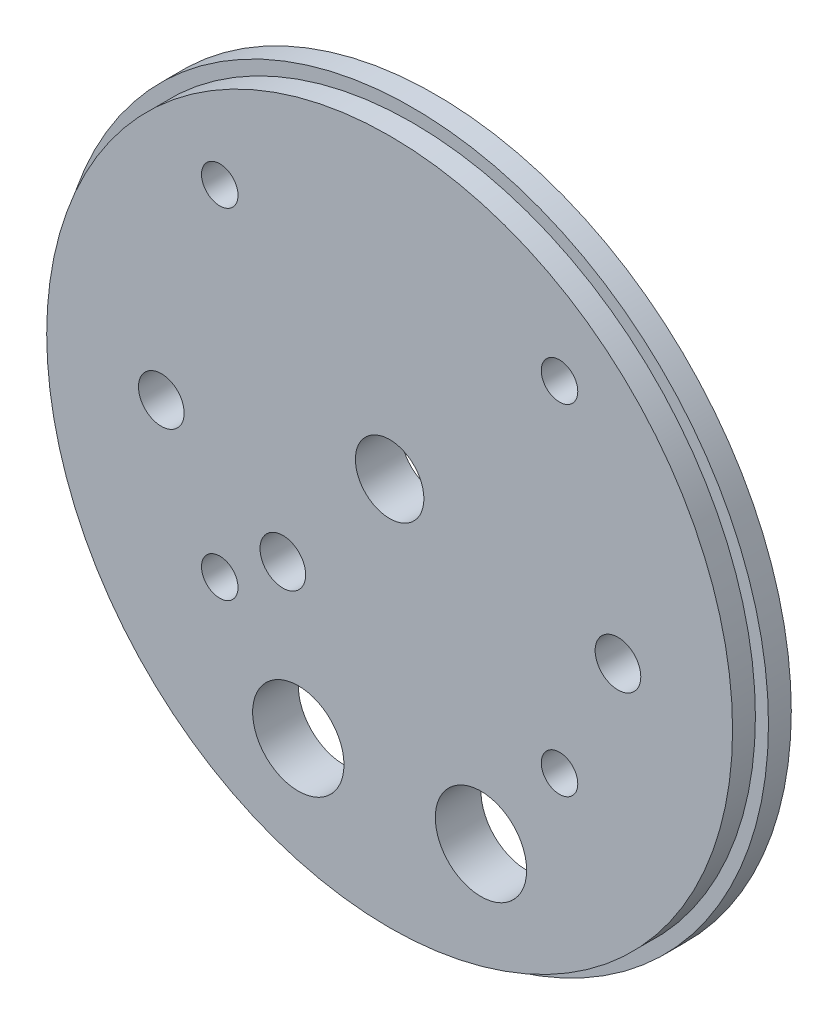
SolidWorks part; units mm, degrees
ref_plane "Front Plane" through (0, 0, 0) normal (0, 0, 1) x (1, 0, 0)
ref_plane "Top Plane" through (0, 0, 0) normal (0, 1, 0) x (1, 0, 0)
ref_plane "Right Plane" through (0, 0, 0) normal (1, 0, 0) x (0, 0, -1)
sketch "Sketch1" plane through (0, 0, 0) normal (0, 0, 1) x (1, 0, 0)
  circle A0 centre (0, 0) radius 49.5046
  point P3 (0, 0)
  dimension "D1" = 99.0092
extrude "Boss-Extrude1" add sketch "Sketch1" along normal blind 3.175
sketch "Sketch2" plane through (0, 0, 3.175) normal (0, 0, 1) x (1, 0, 0)
  circle A0 centre (0, 0) radius 47.6885
  dimension "D1" = 95.377
extrude "Boss-Extrude2" add sketch "Sketch2" along normal blind 3.175
sketch "Sketch3" plane through (0, 0, 6.35) normal (0, 0, 1) x (1, 0, 0)
  circle A0 centre (-12.7, -31.2354) radius 6.35
  circle A1 centre (12.7, -31.2354) radius 6.35
  circle A2 centre (-12.7, -31.2354) radius 12.7 construction
  circle A3 centre (12.7, -31.2354) radius 12.7 construction
  circle A4 centre (12.7, -31.2354) radius 13.97 construction
  circle A5 centre (-12.7, -31.2354) radius 13.97 construction
  circle A6 centre (0, 0) radius 47.6885 construction
  circle A7 centre (-31.75, 0) radius 3.175
  circle A8 centre (31.75, 0) radius 3.175
  circle A9 centre (0, 6.35) radius 15.24 construction
  circle A10 centre (-14.8504, -11.0295) radius 8.89 construction
  circle A11 centre (0, 6.35) radius 16.51 construction
  circle A12 centre (-14.8504, -11.0295) radius 7.62 construction
  circle A13 centre (0, 6.35) radius 4.7625
  circle A14 centre (-14.8504, -11.0295) radius 3.175
  circle A15 centre (-23.622, 29.972) radius 2.54
  circle A16 centre (23.622, 29.972) radius 2.54
  circle A17 centre (23.622, -17.272) radius 2.54
  circle A18 centre (-23.622, -17.272) radius 2.54
  point P31 (0, 0)
  point P32 (0, 0)
  point P33 (0, 0)
  point P34 (0, 0)
  dimension "D1" = 12.7
  dimension "D2" = 12.7
  dimension "D3" = 27.94
  dimension "D4" = 27.94
  dimension "D5" = 25.4
  dimension "D6" = 25.4
  dimension "D7" = 6.35
  dimension "D8" = 6.35
  dimension "D11" = 30.48
  dimension "D12" = 33.02
  dimension "D13" = 15.24
  dimension "D14" = 17.78
  dimension "D15" = 9.525
  dimension "D16" = 6.35
  dimension "D18" = 5.08
  dimension "D9" = 63.5
  dimension "D10" = 31.75
  dimension "D17" = 6.35
  dimension "D19" = 47.244
  dimension "D20" = 47.244
  dimension "D21" = 23.622
  dimension "D22" = 23.622
extrude "Cut-Extrude1" cut sketch "Sketch3" against normal through all
